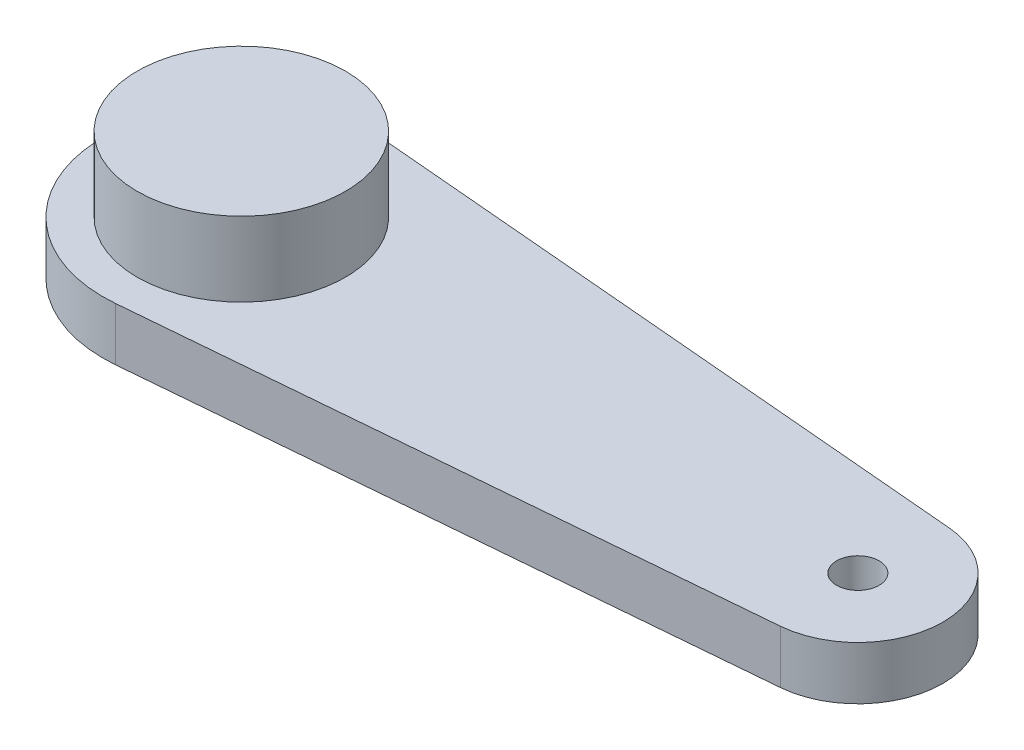
SolidWorks part; units mm, degrees
ref_plane "Front Plane" through (0, 0, 0) normal (0, 0, 1) x (1, 0, 0)
ref_plane "Top Plane" through (0, 0, 0) normal (0, 1, 0) x (1, 0, 0)
ref_plane "Right Plane" through (0, 0, 0) normal (1, 0, 0) x (0, 0, -1)
sketch "Sketch1" plane through (0, 0, 0) normal (0, 1, 0) x (1, 0, 0)
  line L0 (0, 0) -> (29, 0) construction
  line L1 (0.5603, 6.4758) -> (29.3448, 3.9851)
  line L2 (0.5603, -6.4758) -> (29.3448, -3.9851)
  arc A0 (0.5603, 6.4758) -> (0.5603, -6.4758) centre (0, 0) ccw
  arc A1 (29.3448, -3.9851) -> (29.3448, 3.9851) centre (29, 0) ccw
  circle A2 centre (29, 0) radius 1
  dimension "D1" = 13
  dimension "D2" = 8
  dimension "D4" = 2
  dimension "D3" = 29
extrude "Boss-Extrude1" add sketch "Sketch1" along normal blind 2.5
sketch "Sketch2" plane through (0, 2.5, 0) normal (0, 1, 0) x (1, 0, 0)
  circle A0 centre (0, 0) radius 4.9
  dimension "D1" = 9.8
extrude "Boss-Extrude2" add sketch "Sketch2" along normal blind 3.5
